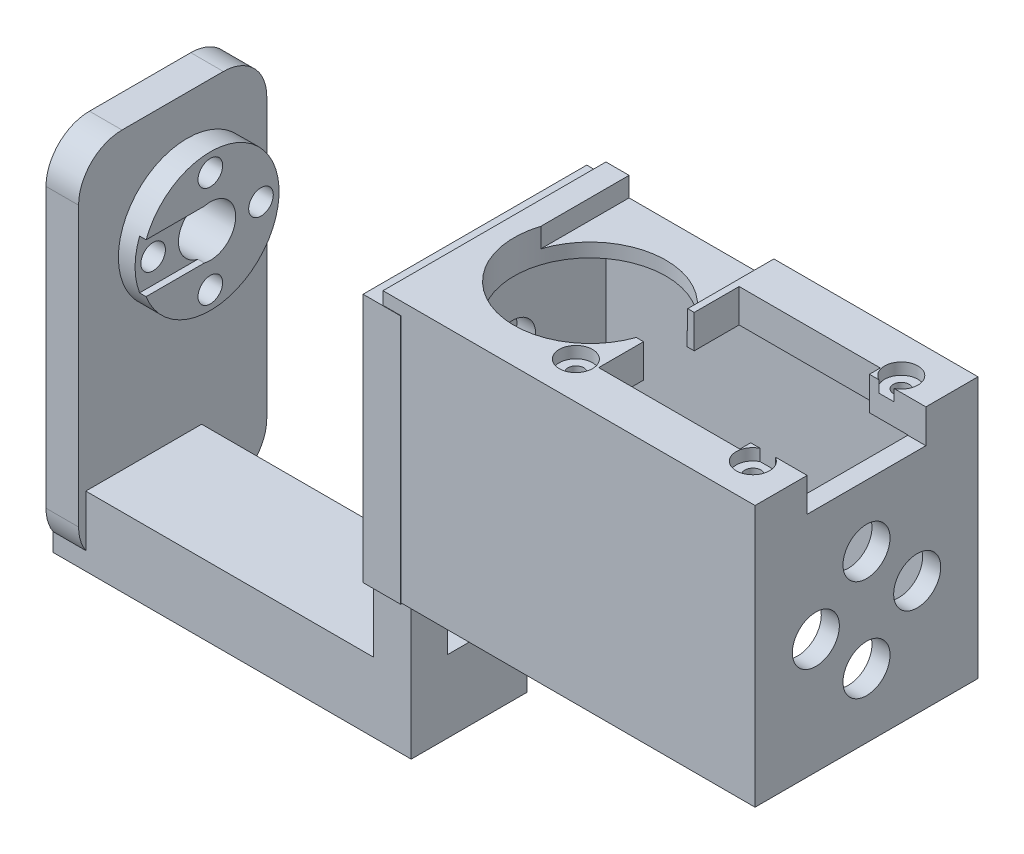
SolidWorks part; units mm, degrees
ref_plane "Front Plane" through (0, 0, 0) normal (0, 0, 1) x (1, 0, 0)
ref_plane "Top Plane" through (0, 0, 0) normal (0, 1, 0) x (1, 0, 0)
ref_plane "Right Plane" through (0, 0, 0) normal (1, 0, 0) x (0, 0, -1)
ref_plane "PX_m15_900" through (-15.9, 0, 0) normal (1, 0, 0) x (0, 0, -1)
sketch "S_prism1" plane through (-15.9, 0, 0) normal (1, 0, 0) x (0, 0, -1)
  line L0 (15.45, 18.45) -> (15.45, -16.05)
  line L1 (15.45, -16.05) -> (-15.45, -16.05)
  line L2 (-15.45, -16.05) -> (-15.45, 18.45)
  line L3 (-15.45, 18.45) -> (15.45, 18.45)
extrude "Boss_1" add sketch "S_prism1" along normal blind 5.2
ref_plane "PX_m55_650" through (-55.65, 0, 0) normal (1, 0, 0) x (0, 0, -1)
sketch "S_cyl2" plane through (-55.65, 0, 0) normal (1, 0, 0) x (0, 0, -1)
  circle A0 centre (0, 0) radius 9.5
  dimension "D1_S_cyl2" = 19
extrude "Boss_2" add sketch "S_cyl2" along normal blind 3.2
ref_plane "PX_m60_150" through (-60.15, 0, 0) normal (1, 0, 0) x (0, 0, -1)
sketch "S_prism3" plane through (-60.15, 0, 0) normal (1, 0, 0) x (0, 0, -1)
  line L0 (11, 9) -> (11, -29.5)
  line L1 (5, -35.5) -> (-9, -35.5)
  line L2 (-15, -29.5) -> (-15, 9)
  line L3 (-9, 15) -> (5, 15)
  arc A0 (5, 15) -> (11, 9) centre (4.9999, 8.9999) cw
  arc A1 (11, -29.5) -> (5, -35.5) centre (4.9999, -29.4999) cw
  arc A2 (-9, -35.5) -> (-15, -29.5) centre (-8.9999, -29.4999) cw
  arc A3 (-15, 9) -> (-9, 15) centre (-8.9999, 8.9999) cw
extrude "Boss_3" add sketch "S_prism3" along normal blind 4.5
ref_plane "PZ_m15_400" through (0, 0, -15.4) normal (0, 0, 1) x (1, 0, 0)
sketch "S_box4" plane through (0, 0, -15.4) normal (0, 0, 1) x (1, 0, 0)
  line L0 (-13.2, -15.9) -> (-10.7, -15.9)
  line L1 (-10.7, -15.9) -> (-10.7, 20.2)
  line L2 (-10.7, 20.2) -> (-13.2, 20.2)
  line L3 (-13.2, 20.2) -> (-13.2, -15.9)
  dimension "P1" = 13.2
  dimension "P2" = 15.9
  dimension "P3" = 10.7
  dimension "P4" = 15.9
  dimension "P5" = 10.7
  dimension "P6" = 20.2
  dimension "P7" = 13.2
  dimension "P8" = 20.2
extrude "Boss_4" add sketch "S_box4" along normal blind 30.8
sketch "S_box5" plane through (0, 0, -15.4) normal (0, 0, 1) x (1, 0, 0)
  line L0 (35.7, -15.9) -> (38.2, -15.9)
  line L1 (38.2, -15.9) -> (38.2, 20.2)
  line L2 (38.2, 20.2) -> (35.7, 20.2)
  line L3 (35.7, 20.2) -> (35.7, -15.9)
  dimension "P1" = 35.7
  dimension "P2" = 15.9
  dimension "P3" = 38.2
  dimension "P4" = 15.9
  dimension "P5" = 38.2
  dimension "P6" = 20.2
  dimension "P7" = 35.7
  dimension "P8" = 20.2
extrude "Boss_5" add sketch "S_box5" along normal blind 30.8
sketch "S_box6" plane through (0, 0, -15.4) normal (0, 0, 1) x (1, 0, 0)
  line L0 (-13.2, -15.9) -> (38.2, -15.9)
  line L1 (38.2, -15.9) -> (38.2, 20.2)
  line L2 (38.2, 20.2) -> (-13.2, 20.2)
  line L3 (-13.2, 20.2) -> (-13.2, -15.9)
  dimension "P1" = 13.2
  dimension "P2" = 15.9
  dimension "P3" = 38.2
  dimension "P4" = 15.9
  dimension "P5" = 38.2
  dimension "P6" = 20.2
  dimension "P7" = 13.2
  dimension "P8" = 20.2
extrude "Boss_6" add sketch "S_box6" along normal blind 2.5
ref_plane "PZ_p12_900" through (0, 0, 12.9) normal (0, 0, 1) x (1, 0, 0)
sketch "S_box7" plane through (0, 0, 12.9) normal (0, 0, 1) x (1, 0, 0)
  line L0 (-13.2, -15.9) -> (38.2, -15.9)
  line L1 (38.2, -15.9) -> (38.2, 20.2)
  line L2 (38.2, 20.2) -> (-13.2, 20.2)
  line L3 (-13.2, 20.2) -> (-13.2, -15.9)
  dimension "P1" = 13.2
  dimension "P2" = 15.9
  dimension "P3" = 38.2
  dimension "P4" = 15.9
  dimension "P5" = 38.2
  dimension "P6" = 20.2
  dimension "P7" = 13.2
  dimension "P8" = 20.2
extrude "Boss_7" add sketch "S_box7" along normal blind 2.5
sketch "S_box8" plane through (0, 0, -15.4) normal (0, 0, 1) x (1, 0, 0)
  line L0 (-13.2, 15.6) -> (38.2, 15.6)
  line L1 (38.2, 15.6) -> (38.2, 20.2)
  line L2 (38.2, 20.2) -> (-13.2, 20.2)
  line L3 (-13.2, 20.2) -> (-13.2, 15.6)
  dimension "P1" = 13.2
  dimension "P2" = 15.6
  dimension "P3" = 38.2
  dimension "P4" = 15.6
  dimension "P5" = 38.2
  dimension "P6" = 20.2
  dimension "P7" = 13.2
  dimension "P8" = 20.2
extrude "Boss_8" add sketch "S_box8" along normal blind 30.8
ref_plane "PZ_p9_000" through (0, 0, 9) normal (0, 0, 1) x (1, 0, 0)
sketch "S_box9" plane through (0, 0, 9) normal (0, 0, 1) x (1, 0, 0)
  line L0 (-15.9, -25.8) -> (-10.7, -25.8)
  line L1 (-10.7, -25.8) -> (-10.7, -16)
  line L2 (-10.7, -16) -> (-15.9, -16)
  line L3 (-15.9, -16) -> (-15.9, -25.8)
  dimension "P1" = 15.9
  dimension "P2" = 25.8
  dimension "P3" = 10.7
  dimension "P4" = 25.8
  dimension "P5" = 10.7
  dimension "P6" = 16
  dimension "P7" = 15.9
  dimension "P8" = 16
extrude "Boss_9" add sketch "S_box9" along normal blind 5
ref_plane "PZ_m2_000" through (0, 0, -2) normal (0, 0, 1) x (1, 0, 0)
sketch "S_box10" plane through (0, 0, -2) normal (0, 0, 1) x (1, 0, 0)
  line L0 (-15.9, -35.3) -> (-10.7, -35.3)
  line L1 (-10.7, -35.3) -> (-10.7, -25.3)
  line L2 (-10.7, -25.3) -> (-15.9, -25.3)
  line L3 (-15.9, -25.3) -> (-15.9, -35.3)
  dimension "P1" = 15.9
  dimension "P2" = 35.3
  dimension "P3" = 10.7
  dimension "P4" = 35.3
  dimension "P5" = 10.7
  dimension "P6" = 25.3
  dimension "P7" = 15.9
  dimension "P8" = 25.3
extrude "Boss_10" add sketch "S_box10" along normal blind 16
sketch "S_box11" plane through (0, 0, -2) normal (0, 0, 1) x (1, 0, 0)
  line L0 (-60.15, -35.3) -> (-10.7, -35.3)
  line L1 (-10.7, -35.3) -> (-10.7, -25.7)
  line L2 (-10.7, -25.7) -> (-60.15, -25.7)
  line L3 (-60.15, -25.7) -> (-60.15, -35.3)
  dimension "P1" = 60.15
  dimension "P2" = 35.3
  dimension "P3" = 10.7
  dimension "P4" = 35.3
  dimension "P5" = 10.7
  dimension "P6" = 25.7
  dimension "P7" = 60.15
  dimension "P8" = 25.7
extrude "Boss_11" add sketch "S_box11" along normal blind 16
ref_plane "PX_m16_000" through (-16, 0, 0) normal (1, 0, 0) x (0, 0, -1)
sketch "S_hole12" plane through (-16, 0, 0) normal (1, 0, 0) x (0, 0, -1)
  circle A0 centre (0, 0) radius 3.5
  dimension "D1_S_hole12" = 7
extrude "Hole_12" cut sketch "S_hole12" along normal blind 5.4
sketch "S_hole13" plane through (-16, 0, 0) normal (1, 0, 0) x (0, 0, -1)
  circle A0 centre (0, -7) radius 1.7
  dimension "D1_S_hole13" = 3.4
  dimension "P2" = 7
extrude "Hole_13" cut sketch "S_hole13" along normal blind 5.4
sketch "S_hole14" plane through (-16, 0, 0) normal (1, 0, 0) x (0, 0, -1)
  circle A0 centre (-7, 0) radius 1.7
  dimension "D1_S_hole14" = 3.4
  dimension "P2" = 7
extrude "Hole_14" cut sketch "S_hole14" along normal blind 5.4
sketch "S_hole15" plane through (-16, 0, 0) normal (1, 0, 0) x (0, 0, -1)
  circle A0 centre (0, 7) radius 1.7
  dimension "D1_S_hole15" = 3.4
  dimension "P2" = 7
extrude "Hole_15" cut sketch "S_hole15" along normal blind 5.4
sketch "S_hole16" plane through (-16, 0, 0) normal (1, 0, 0) x (0, 0, -1)
  circle A0 centre (7, 0) radius 1.7
  dimension "D1_S_hole16" = 3.4
  dimension "P2" = 7
extrude "Hole_16" cut sketch "S_hole16" along normal blind 5.4
ref_plane "PX_m13_300" through (-13.3, 0, 0) normal (1, 0, 0) x (0, 0, -1)
sketch "S_hole17" plane through (-13.3, 0, 0) normal (1, 0, 0) x (0, 0, -1)
  circle A0 centre (0, -7) radius 3.2
  dimension "D1_S_hole17" = 6.4
  dimension "P2" = 7
extrude "Hole_17" cut sketch "S_hole17" along normal blind 2.7
sketch "S_hole18" plane through (-13.3, 0, 0) normal (1, 0, 0) x (0, 0, -1)
  circle A0 centre (-7, 0) radius 3.2
  dimension "D1_S_hole18" = 6.4
  dimension "P2" = 7
extrude "Hole_18" cut sketch "S_hole18" along normal blind 2.7
sketch "S_hole19" plane through (-13.3, 0, 0) normal (1, 0, 0) x (0, 0, -1)
  circle A0 centre (0, 7) radius 3.2
  dimension "D1_S_hole19" = 6.4
  dimension "P2" = 7
extrude "Hole_19" cut sketch "S_hole19" along normal blind 2.7
sketch "S_hole20" plane through (-13.3, 0, 0) normal (1, 0, 0) x (0, 0, -1)
  circle A0 centre (7, 0) radius 3.2
  dimension "D1_S_hole20" = 6.4
  dimension "P2" = 7
extrude "Hole_20" cut sketch "S_hole20" along normal blind 2.7
ref_plane "PX_m60_250" through (-60.25, 0, 0) normal (1, 0, 0) x (0, 0, -1)
sketch "S_hole21" plane through (-60.25, 0, 0) normal (1, 0, 0) x (0, 0, -1)
  circle A0 centre (0, 0) radius 3.5
  dimension "D1_S_hole21" = 7
extrude "Hole_21" cut sketch "S_hole21" along normal blind 7.9
sketch "S_hole22" plane through (-60.25, 0, 0) normal (1, 0, 0) x (0, 0, -1)
  circle A0 centre (0, -7) radius 1.7
  dimension "D1_S_hole22" = 3.4
  dimension "P2" = 7
extrude "Hole_22" cut sketch "S_hole22" along normal blind 7.9
sketch "S_hole23" plane through (-60.25, 0, 0) normal (1, 0, 0) x (0, 0, -1)
  circle A0 centre (-7, 0) radius 1.7
  dimension "D1_S_hole23" = 3.4
  dimension "P2" = 7
extrude "Hole_23" cut sketch "S_hole23" along normal blind 7.9
sketch "S_hole24" plane through (-60.25, 0, 0) normal (1, 0, 0) x (0, 0, -1)
  circle A0 centre (0, 7) radius 1.7
  dimension "D1_S_hole24" = 3.4
  dimension "P2" = 7
extrude "Hole_24" cut sketch "S_hole24" along normal blind 7.9
sketch "S_hole25" plane through (-60.25, 0, 0) normal (1, 0, 0) x (0, 0, -1)
  circle A0 centre (7, 0) radius 1.7
  dimension "D1_S_hole25" = 3.4
  dimension "P2" = 7
extrude "Hole_25" cut sketch "S_hole25" along normal blind 7.9
sketch "S_hole26" plane through (-60.25, 0, 0) normal (1, 0, 0) x (0, 0, -1)
  circle A0 centre (0, -7) radius 3.2
  dimension "D1_S_hole26" = 6.4
  dimension "P2" = 7
extrude "Hole_26" cut sketch "S_hole26" along normal blind 2.1
sketch "S_hole27" plane through (-60.25, 0, 0) normal (1, 0, 0) x (0, 0, -1)
  circle A0 centre (-7, 0) radius 3.2
  dimension "D1_S_hole27" = 6.4
  dimension "P2" = 7
extrude "Hole_27" cut sketch "S_hole27" along normal blind 2.1
sketch "S_hole28" plane through (-60.25, 0, 0) normal (1, 0, 0) x (0, 0, -1)
  circle A0 centre (0, 7) radius 3.2
  dimension "D1_S_hole28" = 6.4
  dimension "P2" = 7
extrude "Hole_28" cut sketch "S_hole28" along normal blind 2.1
sketch "S_hole29" plane through (-60.25, 0, 0) normal (1, 0, 0) x (0, 0, -1)
  circle A0 centre (7, 0) radius 3.2
  dimension "D1_S_hole29" = 6.4
  dimension "P2" = 7
extrude "Hole_29" cut sketch "S_hole29" along normal blind 2.1
sketch "S_cut30" plane through (0, 0, 0) normal (0, 0, 1) x (1, 0, 0)
  line L0 (-53.35, -3.4) -> (-52.35, -3.4)
  line L1 (-52.35, -3.4) -> (-52.35, 3.4)
  line L2 (-52.35, 3.4) -> (-53.35, 3.4)
  line L3 (-53.35, 3.4) -> (-53.35, -3.4)
  dimension "P1" = 53.35
  dimension "P2" = 3.4
  dimension "P3" = 52.35
  dimension "P4" = 3.4
  dimension "P5" = 52.35
  dimension "P6" = 3.4
  dimension "P7" = 53.35
  dimension "P8" = 3.4
extrude "Pocket_30" cut sketch "S_cut30" along normal blind 10
ref_plane "PY_p15_500" through (0, 15.5, 0) normal (0, 1, 0) x (1, 0, 0)
sketch "S_hole31" plane through (0, 15.5, 0) normal (0, 1, 0) x (1, 0, 0)
  circle A0 centre (0, 0) radius 10.5
  dimension "D1_S_hole31" = 21
extrude "Hole_31" cut sketch "S_hole31" along normal blind 4.8
ref_plane "PZ_m9_700" through (0, 0, -9.7) normal (0, 0, 1) x (1, 0, 0)
sketch "S_cut32" plane through (0, 0, -9.7) normal (0, 0, 1) x (1, 0, 0)
  line L0 (10.9, 15.55) -> (30.4, 15.55)
  line L1 (30.4, 15.55) -> (30.4, 20.3)
  line L2 (30.4, 20.3) -> (10.9, 20.3)
  line L3 (10.9, 20.3) -> (10.9, 15.55)
  dimension "P1" = 10.9
  dimension "P2" = 15.55
  dimension "P3" = 30.4
  dimension "P4" = 15.55
  dimension "P5" = 30.4
  dimension "P6" = 20.3
  dimension "P7" = 10.9
  dimension "P8" = 20.3
extrude "Pocket_32" cut sketch "S_cut32" along normal blind 19.4
ref_plane "PZ_m8_200" through (0, 0, -8.2) normal (0, 0, 1) x (1, 0, 0)
sketch "S_cut33" plane through (0, 0, -8.2) normal (0, 0, 1) x (1, 0, 0)
  line L0 (30.4, 15.55) -> (38.7, 15.55)
  line L1 (38.7, 15.55) -> (38.7, 20.3)
  line L2 (38.7, 20.3) -> (30.4, 20.3)
  line L3 (30.4, 20.3) -> (30.4, 15.55)
  dimension "P1" = 30.4
  dimension "P2" = 15.55
  dimension "P3" = 38.7
  dimension "P4" = 15.55
  dimension "P5" = 38.7
  dimension "P6" = 20.3
  dimension "P7" = 30.4
  dimension "P8" = 20.3
extrude "Pocket_33" cut sketch "S_cut33" along normal blind 16.4
ref_plane "PZ_m3_500" through (0, 0, -3.5) normal (0, 0, 1) x (1, 0, 0)
sketch "S_cut34" plane through (0, 0, -3.5) normal (0, 0, 1) x (1, 0, 0)
  line L0 (0, 15.55) -> (11, 15.55)
  line L1 (11, 15.55) -> (11, 20.3)
  line L2 (11, 20.3) -> (0, 20.3)
  line L3 (0, 20.3) -> (0, 15.55)
  dimension "P1" = 15.55
  dimension "P2" = 11
  dimension "P3" = 15.55
  dimension "P4" = 11
  dimension "P5" = 20.3
  dimension "P6" = 20.3
extrude "Pocket_34" cut sketch "S_cut34" along normal blind 7
ref_plane "PZ_m15_900" through (0, 0, -15.9) normal (0, 0, 1) x (1, 0, 0)
sketch "S_cut35" plane through (0, 0, -15.9) normal (0, 0, 1) x (1, 0, 0)
  line L0 (-10, 17.5) -> (10, 17.5)
  line L1 (10, 17.5) -> (10, 20.4)
  line L2 (10, 20.4) -> (-10, 20.4)
  line L3 (-10, 20.4) -> (-10, 17.5)
  dimension "P1" = 10
  dimension "P2" = 17.5
  dimension "P3" = 10
  dimension "P4" = 17.5
  dimension "P5" = 10
  dimension "P6" = 20.4
  dimension "P7" = 10
  dimension "P8" = 20.4
extrude "Pocket_35" cut sketch "S_cut35" along normal blind 15.9
sketch "S_hole36" plane through (0, 15.5, 0) normal (0, 1, 0) x (1, 0, 0)
  circle A0 centre (8.3, -10.25) radius 1.1
  dimension "D1_S_hole36" = 2.2
  dimension "P2" = 8.3
  dimension "P3" = 10.25
extrude "Hole_36" cut sketch "S_hole36" along normal blind 4.8
ref_plane "PY_p18_600" through (0, 18.6, 0) normal (0, 1, 0) x (1, 0, 0)
sketch "S_hole37" plane through (0, 18.6, 0) normal (0, 1, 0) x (1, 0, 0)
  circle A0 centre (8.3, -10.25) radius 2.3
  dimension "D1_S_hole37" = 4.6
  dimension "P2" = 8.3
  dimension "P3" = 10.25
extrude "Hole_37" cut sketch "S_hole37" along normal blind 1.7
sketch "S_hole38" plane through (0, 15.5, 0) normal (0, 1, 0) x (1, 0, 0)
  circle A0 centre (32.75, 10.25) radius 1.1
  dimension "D1_S_hole38" = 2.2
  dimension "P2" = 32.75
  dimension "P3" = 10.25
extrude "Hole_38" cut sketch "S_hole38" along normal blind 4.8
sketch "S_hole39" plane through (0, 18.6, 0) normal (0, 1, 0) x (1, 0, 0)
  circle A0 centre (32.75, 10.25) radius 2.3
  dimension "D1_S_hole39" = 4.6
  dimension "P2" = 32.75
  dimension "P3" = 10.25
extrude "Hole_39" cut sketch "S_hole39" along normal blind 1.7
sketch "S_hole40" plane through (0, 15.5, 0) normal (0, 1, 0) x (1, 0, 0)
  circle A0 centre (32.75, -10.25) radius 1.1
  dimension "D1_S_hole40" = 2.2
  dimension "P2" = 32.75
  dimension "P3" = 10.25
extrude "Hole_40" cut sketch "S_hole40" along normal blind 4.8
sketch "S_hole41" plane through (0, 18.6, 0) normal (0, 1, 0) x (1, 0, 0)
  circle A0 centre (32.75, -10.25) radius 2.3
  dimension "D1_S_hole41" = 4.6
  dimension "P2" = 32.75
  dimension "P3" = 10.25
extrude "Hole_41" cut sketch "S_hole41" along normal blind 1.7
ref_plane "PX_p35_600" through (35.6, 0, 0) normal (1, 0, 0) x (0, 0, -1)
sketch "S_hole42" plane through (35.6, 0, 0) normal (1, 0, 0) x (0, 0, -1)
  circle A0 centre (0, -7) radius 3.25
  dimension "D1_S_hole42" = 6.5
  dimension "P2" = 7
extrude "Hole_42" cut sketch "S_hole42" along normal blind 2.7
sketch "S_hole43" plane through (35.6, 0, 0) normal (1, 0, 0) x (0, 0, -1)
  circle A0 centre (-7, 0) radius 3.25
  dimension "D1_S_hole43" = 6.5
  dimension "P2" = 7
extrude "Hole_43" cut sketch "S_hole43" along normal blind 2.7
sketch "S_hole44" plane through (35.6, 0, 0) normal (1, 0, 0) x (0, 0, -1)
  circle A0 centre (0, 7) radius 3.25
  dimension "D1_S_hole44" = 6.5
  dimension "P2" = 7
extrude "Hole_44" cut sketch "S_hole44" along normal blind 2.7
sketch "S_hole45" plane through (35.6, 0, 0) normal (1, 0, 0) x (0, 0, -1)
  circle A0 centre (7, 0) radius 3.25
  dimension "D1_S_hole45" = 6.5
  dimension "P2" = 7
extrude "Hole_45" cut sketch "S_hole45" along normal blind 2.7
equation "\"plate_t\" = 3"
equation "\"clearance\" = 0.5"
